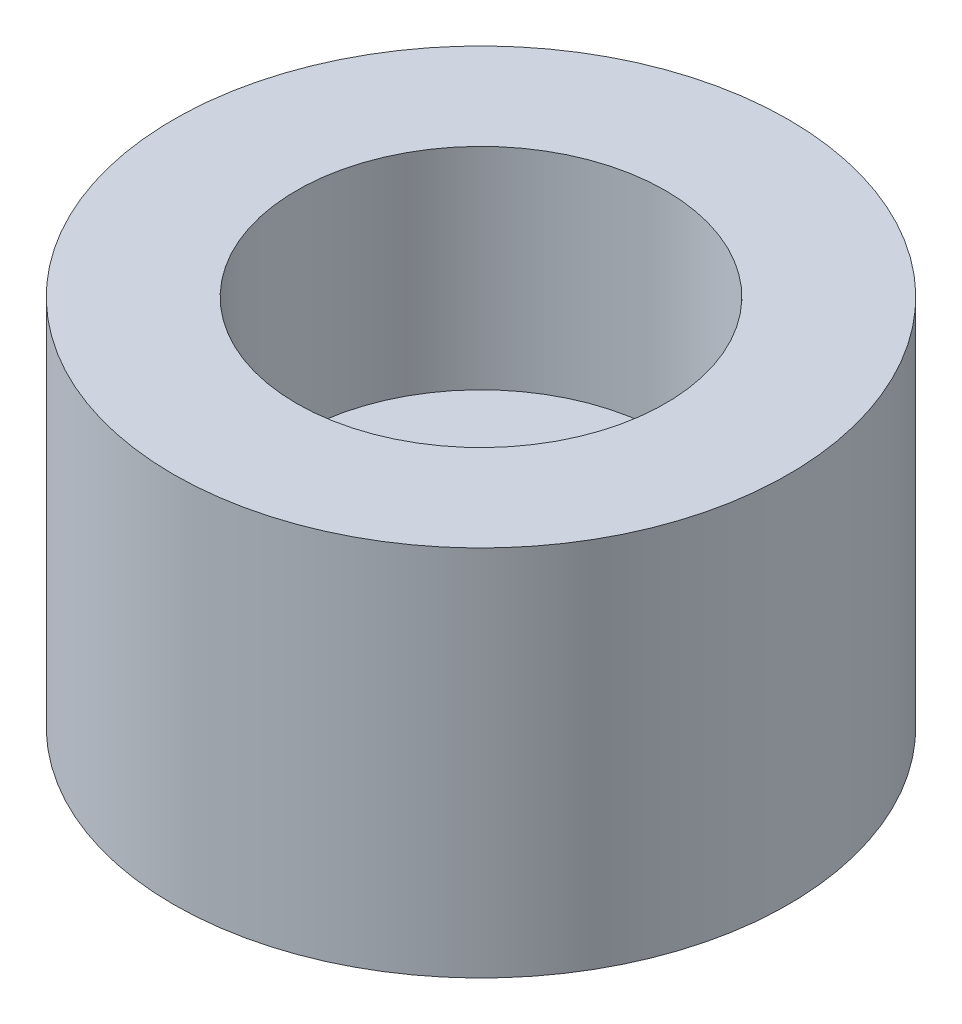
SolidWorks part; units mm, degrees
ref_plane "Front Plane" through (0, 0, 0) normal (0, 0, 1) x (1, 0, 0)
ref_plane "Top Plane" through (0, 0, 0) normal (0, 1, 0) x (1, 0, 0)
ref_plane "Right Plane" through (0, 0, 0) normal (1, 0, 0) x (0, 0, -1)
sketch "Sketch1" plane through (0, 0, 0) normal (0, 1, 0) x (1, 0, 0)
  circle A0 centre (0, 0) radius 4.375
  circle A1 centre (0, 0) radius 2.625
  dimension "D1" = 8.75
  dimension "D2" = 5.25
extrude "Boss-Extrude1" add sketch "Sketch1" along normal blind 3
sketch "Sketch2" plane through (0, 0, 0) normal (0, -1, 0) x (1, 0, 0)
  line L0 (0, 0) -> (0, 4.375) construction
  circle A2 centre (0, 0) radius 1.425
  circle A8 centre (0, 0) radius 4.375
  circle A9 centre (0, 0) radius 4.375 construction
  dimension "D1" = 2.85
extrude "Boss-Extrude2" add sketch "Sketch2" along normal blind 2.3
